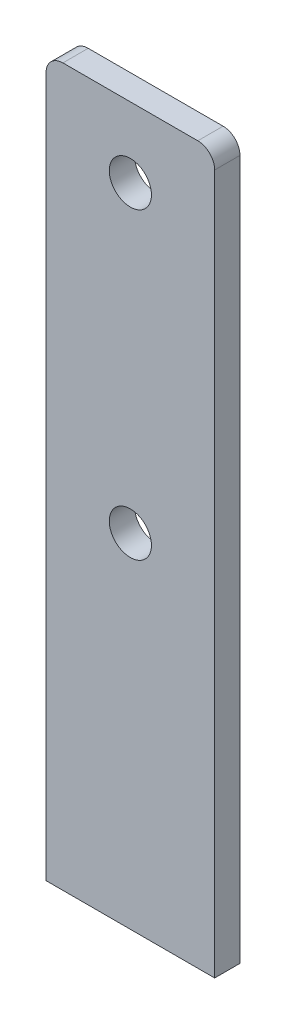
SolidWorks part; units mm, degrees
ref_plane "Alzado" through (0, 0, 0) normal (0, 0, 1) x (1, 0, 0)
ref_plane "Planta" through (0, 0, 0) normal (0, 1, 0) x (1, 0, 0)
ref_plane "Vista lateral" through (0, 0, 0) normal (1, 0, 0) x (0, 0, -1)
sketch "Croquis1" plane through (0, 0, 0) normal (0, 0, 1) x (1, 0, 0)
  line L5 (20, 0) -> (20, 83)
  line L6 (20, 0) -> (0, 0)
  line L7 (10, 0) -> (10, 85)
  line L8 (10, 20) -> (10, 79.19) construction
  line L9 (18, 85) -> (2, 85)
  line L10 (0, 0) -> (0, 83)
  line L11 (10, 0) -> (10, 10) construction
  circle A0 centre (10, 76.69) radius 2.5
  circle A1 centre (10, 40.69) radius 2.5
  arc A3 (2, 85) -> (0, 83) centre (2, 83) ccw
  arc A4 (18, 85) -> (20, 83) centre (18, 83) cw
  point P14 (0, 85)
  dimension "D2" = 5
  dimension "D8" = 2
  dimension "D1" = 10
  dimension "D4" = 30.69
  dimension "D6" = 85
  dimension "D7" = 10
  dimension "D3" = 2
extrude "Saliente-Extruir1" add sketch "Croquis1" along normal blind 3
